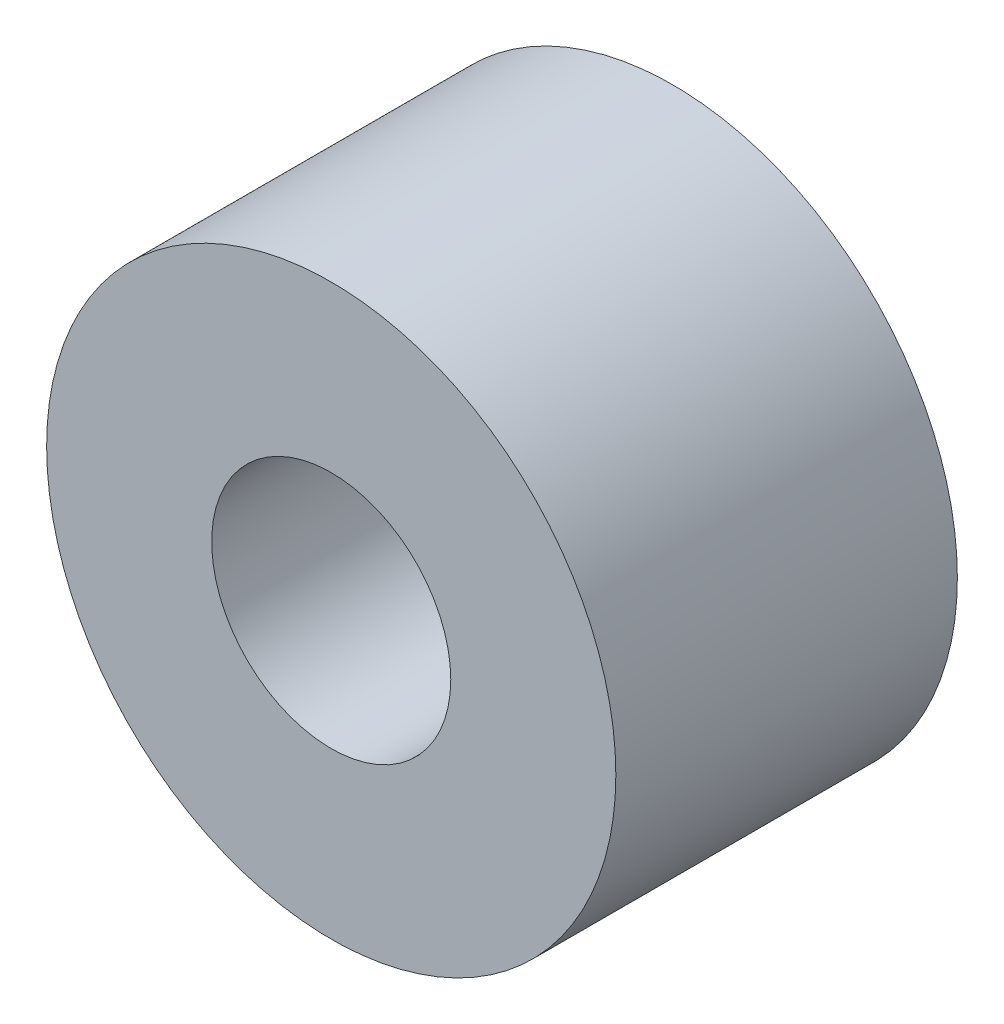
SolidWorks part; units mm, degrees
ref_plane "前视基准面" through (0, 0, 0) normal (0, 0, 1) x (1, 0, 0)
ref_plane "上视基准面" through (0, 0, 0) normal (0, 1, 0) x (1, 0, 0)
ref_plane "右视基准面" through (0, 0, 0) normal (1, 0, 0) x (0, 0, -1)
other "Configuration Table"
sketch "草图1" plane through (0, 0, 0) normal (0, 0, 1) x (1, 0, 0)
  circle A0 centre (0, 0) radius 10
  circle A1 centre (0, 0) radius 4.2
extrude "Hand_knob_simplified" add sketch "草图1" along normal blind 12
